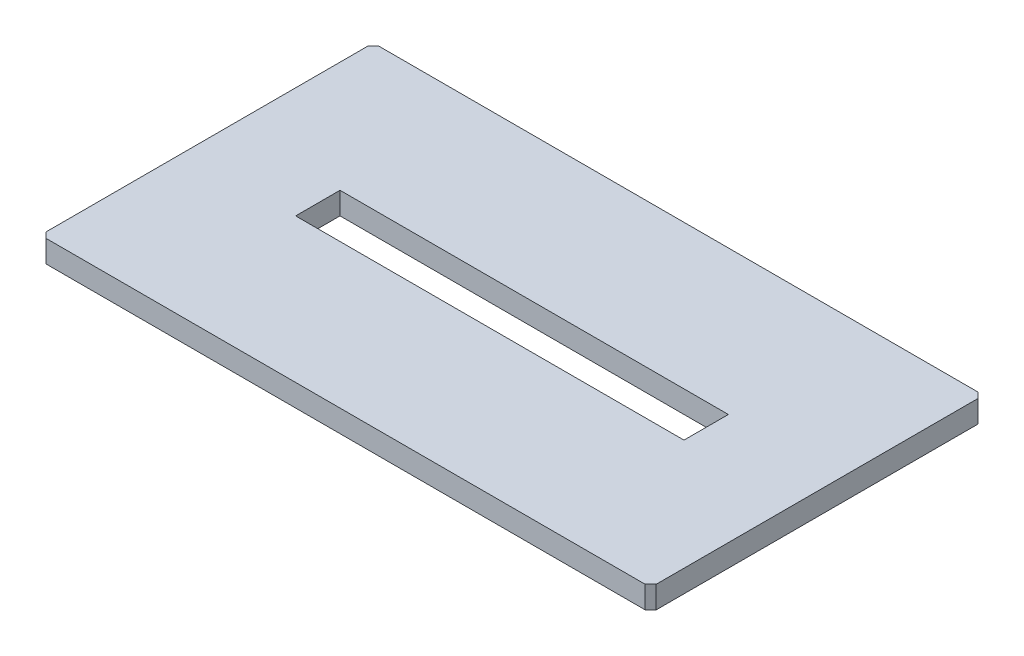
SolidWorks part; units mm, degrees
material "Сталь 3 ГОСТ 535-88"
ref_plane "Спереди" through (0, 0, 0) normal (0, 0, 1) x (1, 0, 0)
ref_plane "Сверху" through (0, 0, 0) normal (0, 1, 0) x (1, 0, 0)
ref_plane "Справа" through (0, 0, 0) normal (1, 0, 0) x (0, 0, -1)
sketch "Эскиз1" plane through (0, 0, 0) normal (0, 1, 0) x (1, 0, 0)
  line L1 (-275, -150) -> (275, -150)
  line L2 (-275, -150) -> (-275, 150)
  line L3 (-275, 150) -> (275, 150)
  line L4 (275, -150) -> (275, 150)
  line L5 (0, 150) -> (0, -150) construction
  line L6 (-275, 0) -> (275, 0) construction
  line L7 (-175, -20) -> (175, -20)
  line L8 (-175, -20) -> (-175, 20)
  line L9 (-175, 20) -> (175, 20)
  line L10 (175, -20) -> (175, 20)
  line L11 (0, 20) -> (0, -20) construction
  line L12 (-175, 0) -> (175, 0) construction
  point P0 (0, 0)
  point P4 (0, 0)
  dimension "D1" = 550
  dimension "D2" = 300
  dimension "D3" = 40
  dimension "D4" = 350
extrude "Бобышка-Вытянуть1" add sketch "Эскиз1" against normal blind 20
chamfer "Фаска1" distance 5 angle 45 4 edges at (-275, -10, -150) (-275, -10, 150) (275, -10, -150) (275, -10, 150)
sketch "Эскиз2" plane through (0, -20, 0) normal (0, 1, 0) x (-1, 0, 0)
  line L0 (-289.1303, 0) -> (289.1303, 0) construction
  line L1 (0, 46.6825) -> (0, -46.6825) construction
  line L2 (270, 150) -> (-270, 150) construction
  line L3 (275, -145) -> (275, 145) construction
  circle A0 centre (240, 115) radius 5
  circle A1 centre (-240, 115) radius 5
  circle A2 centre (-240, -115) radius 5
  circle A3 centre (240, -115) radius 5
  dimension "D3" = 10
  dimension "D1" = 35
  dimension "D2" = 35
extrude "Вырез-Вытянуть1" cut sketch "Эскиз2" along normal offset from surface (17 mm away) 3 up to face at (0, 0, 0)
cosmetic thread "Условное изображение резьбы2" parameters "D2"=22
cosmetic thread "Условное изображение резьбы3" parameters "D2"=12
cosmetic thread "Условное изображение резьбы4" parameters "D2"=12
cosmetic thread "Условное изображение резьбы5" parameters "D2"=12
equation "\"D2@Эскиз2\"=-\"D1@Эскиз2\""
